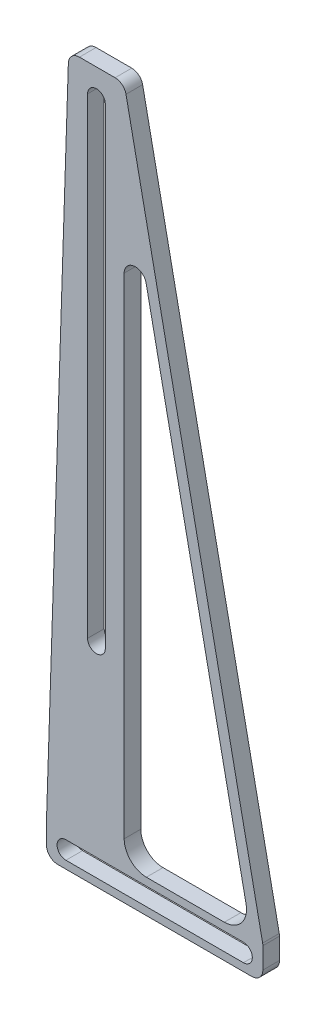
SolidWorks part; units mm, degrees
ref_plane "前视基准面" through (0, 0, 0) normal (0, 0, 1) x (1, 0, 0)
ref_plane "上视基准面" through (0, 0, 0) normal (0, 1, 0) x (1, 0, 0)
ref_plane "右视基准面" through (0, 0, 0) normal (1, 0, 0) x (0, 0, -1)
sketch "草图1" plane through (0, 0, 0) normal (0, 0, 1) x (1, 0, 0)
  line L0 (0, 0) -> (39, 0)
  line L1 (39, 0) -> (39, 6)
  line L2 (39, 6) -> (14, 6)
  line L3 (14, 6) -> (14, 128)
  line L4 (14, 128) -> (4, 128)
  line L5 (4, 128) -> (4, 6)
  line L6 (4, 6) -> (0, 6)
  line L7 (0, 6) -> (0, 0)
  line L8 (3.5, 3) -> (35.5, 3) construction
  line L9 (3.5, 4.6) -> (35.5, 4.6)
  line L10 (3.5, 1.4) -> (35.5, 1.4)
  line L11 (9, 38) -> (9, 123) construction
  line L12 (7.4, 38) -> (7.4, 123)
  line L13 (10.6, 38) -> (10.6, 123)
  arc A0 (3.5, 4.6) -> (3.5, 1.4) centre (3.5, 3) ccw
  arc A1 (35.5, 1.4) -> (35.5, 4.6) centre (35.5, 3) ccw
  arc A2 (7.4, 38) -> (10.6, 38) centre (9, 38) ccw
  arc A3 (10.6, 123) -> (7.4, 123) centre (9, 123) ccw
  point P11 (19.5, 3)
  point P17 (19.5, 0)
  point P18 (9, 80.5)
  point P19 (39, 3)
  point P26 (9, 128)
  dimension "D1" = 128
  dimension "D2" = 10
  dimension "D3" = 4
  dimension "D4" = 25
  dimension "D5" = 6
  dimension "D6" = 3.2
  dimension "D7" = 3.5
  dimension "D8" = 5
  dimension "D9" = 90
extrude "凸台-拉伸1" add sketch "草图1" along normal blind 3
sketch "草图2" plane through (0, 0, 3) normal (0, 0, 1) x (1, 0, 0)
  line L0 (0, 6) -> (4, 128)
  line L1 (14, 128) -> (39, 6)
  line L2 (39, 6) -> (36.9584, 6)
  line L3 (39, 6) -> (14, 6) construction
  line L4 (36.9584, 6) -> (14, 118.0372)
  line L5 (14, 6) -> (14, 128) construction
  line L6 (14, 118.0372) -> (14, 128)
  line L7 (0, 6) -> (4, 6)
  line L8 (4, 6) -> (0, 6) construction
  line L10 (4, 128) -> (4, 6) construction
  line L11 (4, 6) -> (4, 128)
  dimension "D2" = 2
extrude "凸台-拉伸2" add sketch "草图2" against normal up to surface (3 mm away) up to face at (19.5, 3, 0)
fillet "圆角1" radius 2 5 edges at (14, 128, 1.5) (4, 128, 1.5) (14, 118.0372, 1.5) (39, 6, 1.5) (0, 6, 1.5)
fillet "圆角2" radius 4 2 edges at (36.9584, 6, 1.5) (14, 6, 1.5)
fillet "圆角3" radius 2 2 edges at (0, 0, 1.5) (39, 0, 1.5)
sketch "草图3" plane through (0, 0, 3) normal (0, 0, 1) x (1, 0, 0)
  line L1 (9, 38) -> (9, 123) construction
  line L2 (3.5, 3) -> (35.5, 3) construction
  arc A0 (3.5, 4.6) -> (3.5, 1.4) centre (3.5, 3) ccw construction
  arc A1 (35.5, 1.4) -> (35.5, 4.6) centre (35.5, 3) ccw construction
sketch "草图4" plane through (0, 0, 0) normal (0, 0, -1) x (-1, 0, 0)
  line L1 (-9, 38) -> (-9, 123) construction
  line L3 (-9, 38) -> (-9, 123) construction
